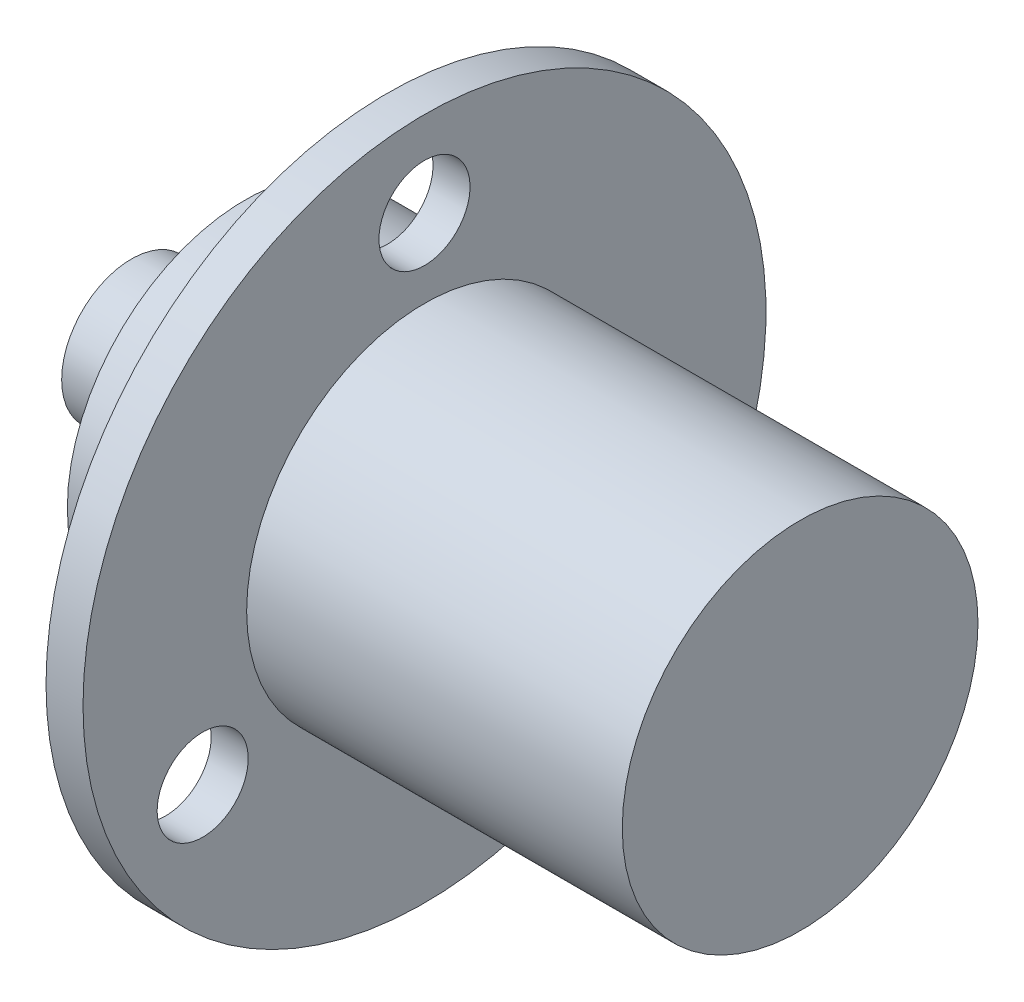
SolidWorks part; units mm, degrees
ref_plane "前视基准面" through (0, 0, 0) normal (0, 0, 1) x (1, 0, 0)
ref_plane "上视基准面" through (0, 0, 0) normal (0, 1, 0) x (1, 0, 0)
ref_plane "右视基准面" through (0, 0, 0) normal (1, 0, 0) x (0, 0, -1)
other "Configuration Table"
sketch "草图1" plane through (0, 0, 0) normal (0, 0, 1) x (1, 0, 0)
  line L0 (-8.0796, 0) -> (12.0867, 0) construction
  line L1 (-9, 0) -> (-9, 2.45)
  line L2 (-9, 2.45) -> (-5, 2.45)
  line L3 (-5, 2.45) -> (-5, 6.25)
  line L4 (-5, 6.25) -> (0, 6.25)
  line L5 (0, 6.25) -> (0, 12)
  line L6 (0, 12) -> (1.3, 12)
  line L7 (1.3, 12) -> (1.3, 6.25)
  line L8 (1.3, 6.25) -> (14.5, 6.25)
  line L9 (14.5, 6.25) -> (14.5, 0)
  line L10 (14.5, 0) -> (-9, 0)
  dimension "D1" = 2.45
  dimension "D2" = 4
  dimension "D3" = 6.25
  dimension "D4" = 12
  dimension "D5" = 6.25
  dimension "D6" = 5
  dimension "D7" = 1.3
  dimension "D8" = 19.5
revolve "旋转1" add sketch "草图1" angle 360 about L0
sketch "草图2" plane through (0, 0, 0) normal (-1, 0, 0) x (0, 0, 1)
  circle A0 centre (0, 0) radius 9 construction
  circle A1 centre (0, 9) radius 1.6
  circle A2 centre (7.7942, -4.5) radius 1.6
  circle A3 centre (0, 0) radius 9 construction
  circle A4 centre (-7.7942, -4.5) radius 1.6
  circle A5 centre (0, 0) radius 9 construction
  point P14 (0, 0)
  dimension "D1" = 18
  dimension "D2" = 3.2
  dimension "D3" = 3
extrude "切除-拉伸1" cut sketch "草图2" against normal blind 10
